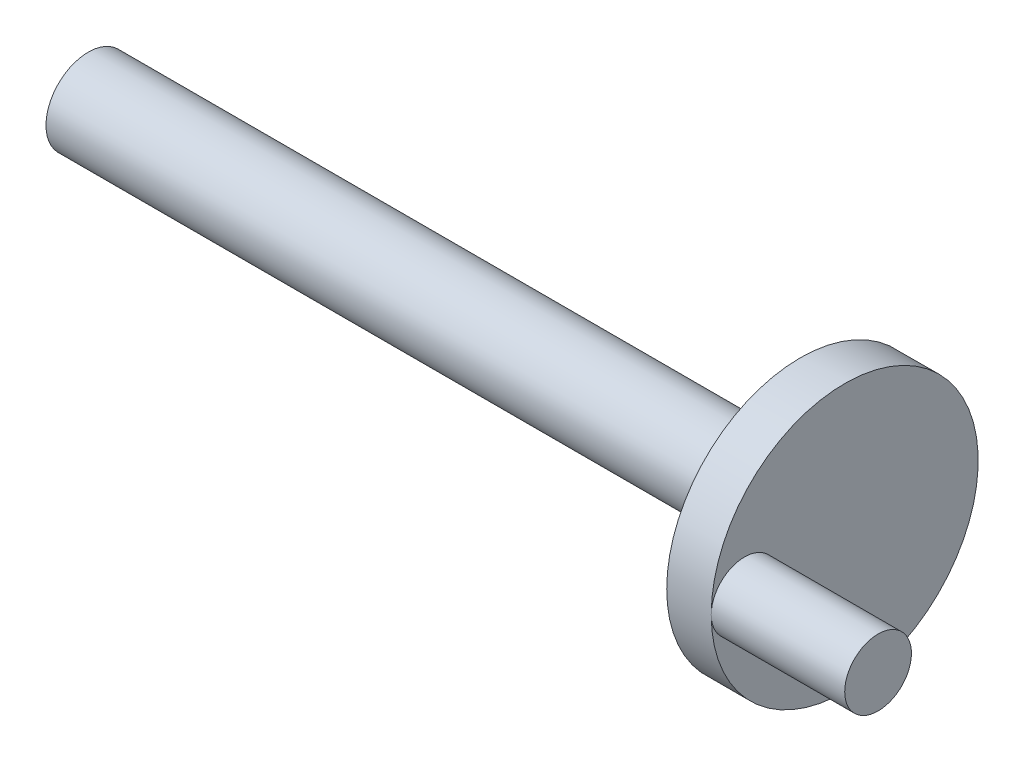
SolidWorks part; units mm, degrees
ref_plane "Front Plane" through (0, 0, 0) normal (0, 0, 1) x (1, 0, 0)
ref_plane "Top Plane" through (0, 0, 0) normal (0, 1, 0) x (1, 0, 0)
ref_plane "Right Plane" through (0, 0, 0) normal (1, 0, 0) x (0, 0, -1)
sketch "Sketch1" plane through (0, 0, 0) normal (1, 0, 0) x (0, 0, -1)
  line L0 (1.905, 1.4811) -> (1.905, -1.4811)
  arc A0 (1.905, 1.4811) -> (1.905, -1.4811) centre (0, 0) ccw
  dimension "D1" = 4.826
  dimension "D2" = 1.905
extrude "Boss-Extrude1" add sketch "Sketch1" along normal mid plane 40.64
sketch "Sketch2" plane through (20.32, 0, 0) normal (1, 0, 0) x (0, 0, -1)
  circle A0 centre (0, 0) radius 7.62
  dimension "D1" = 15.24
extrude "Boss-Extrude2" add sketch "Sketch2" along normal blind 2.54
sketch "Sketch3" plane through (22.86, 0, 0) normal (1, 0, 0) x (0, 0, -1)
  circle A0 centre (-5.715, 0) radius 1.905
  circle A1 centre (0, 0) radius 7.62 construction
  dimension "D1" = 3.81
extrude "Boss-Extrude3" add sketch "Sketch3" along normal blind 7.62
